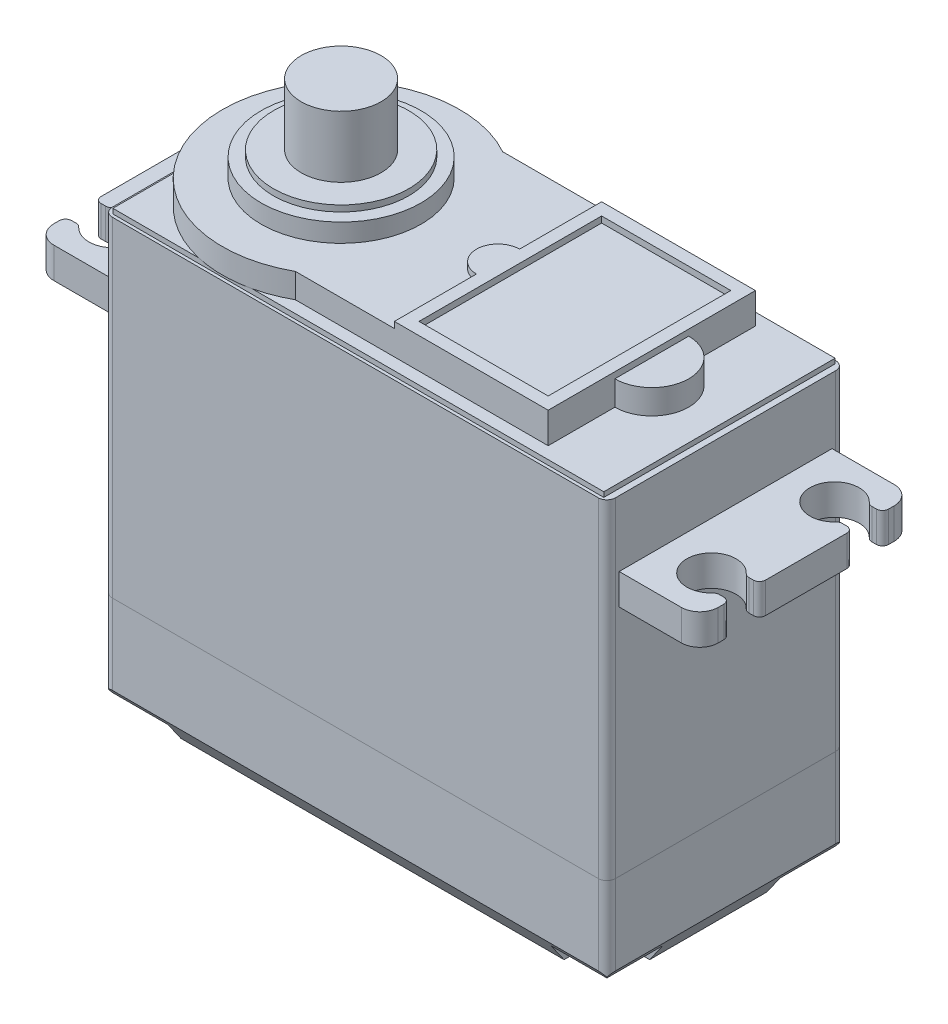
SolidWorks part; units mm, degrees
ref_plane "Front Plane" through (0, 0, 0) normal (0, 0, 1) x (1, 0, 0)
ref_plane "Top Plane" through (0, 0, 0) normal (0, 1, 0) x (1, 0, 0)
ref_plane "Right Plane" through (0, 0, 0) normal (1, 0, 0) x (0, 0, -1)
sketch "Sketch1" plane through (0, 0, 0) normal (0, 0, 1) x (1, 0, 0)
  line L1 (-20.45, 10) -> (20.45, 10)
  line L2 (-20.45, 10) -> (-20.45, -10)
  line L3 (-20.45, -10) -> (20.45, -10)
  line L4 (20.45, 10) -> (20.45, -10)
  line L5 (-20.45, 10) -> (20.45, -10) construction
  line L6 (-20.45, -10) -> (20.45, 10) construction
  point P0 (0, 0)
  dimension "D1" = 20
  dimension "D2" = 40.9
extrude "Boss-Extrude1" add sketch "Sketch1" along normal blind 19.3
sketch "Sketch2" plane through (0, 10, 0) normal (0, 1, 0) x (1, 0, 0)
  line L4 (20.45, 0) -> (-20.45, 0)
  line L5 (-20.45, 0) -> (-20.45, -19.3)
  line L6 (-20.45, -19.3) -> (20.45, -19.3)
  line L7 (20.45, -19.3) -> (20.45, 0)
  line L8 (20.45, 0) -> (-20.45, 0)
  line L9 (-20.45, 0) -> (-20.45, -19.3)
  line L10 (-20.45, -19.3) -> (20.45, -19.3)
  line L11 (20.45, -19.3) -> (20.45, 0)
  dimension "D1" = 0
extrude "Boss-Extrude2" add sketch "Sketch2" along normal blind 6.8 separate body
sketch "Sketch3" plane through (0, -10, 0) normal (0, -1, 0) x (1, 0, 0)
  line L4 (-20.45, 0) -> (20.45, 0)
  line L5 (20.45, 0) -> (20.45, 19.3)
  line L6 (20.45, 19.3) -> (-20.45, 19.3)
  line L7 (-20.45, 19.3) -> (-20.45, 0)
  line L8 (-20.45, 0) -> (20.45, 0)
  line L9 (20.45, 0) -> (20.45, 19.3)
  line L10 (20.45, 19.3) -> (-20.45, 19.3)
  line L11 (-20.45, 19.3) -> (-20.45, 0)
  dimension "D1" = 0
extrude "Boss-Extrude3" add sketch "Sketch3" along normal blind 8.5 separate body
chamfer "Chamfer1" distance 2 angle 35 4 edges at (0, -18.5, 19.3) (20.45, -18.5, 9.65) (0, -18.5, 0) (-20.45, -18.5, 9.65)
sketch "Sketch4" plane through (0, -18.5, 0) normal (0, -1, 0) x (1, 0, 0)
  line L0 (0, 0) -> (0, 19.3) construction
  line L1 (-20.45, 19.3) -> (-15.57, 19.3)
  line L2 (-20.45, 19.3) -> (-20.45, 14.42)
  line L3 (-20.45, 14.42) -> (-17.57, 14.42)
  line L4 (-15.57, 19.3) -> (-15.57, 16.42)
  line L5 (-20.45, 19.3) -> (20.45, 19.3) construction
  line L6 (-20.45, 9.65) -> (20.45, 9.65) construction
  line L7 (-20.45, 0) -> (-20.45, 19.3) construction
  line L8 (20.45, 19.3) -> (20.45, 0) construction
  line L9 (20.45, 14.42) -> (17.57, 14.42)
  line L10 (15.57, 19.3) -> (15.57, 16.42)
  line L11 (20.45, 19.3) -> (15.57, 19.3)
  line L12 (20.45, 19.3) -> (20.45, 14.42)
  line L13 (20.45, 0) -> (20.45, 4.88)
  line L14 (20.45, 0) -> (15.57, 0)
  line L15 (15.57, 0) -> (15.57, 2.88)
  line L16 (20.45, 4.88) -> (17.57, 4.88)
  line L17 (-20.45, 4.88) -> (-17.57, 4.88)
  line L18 (-15.57, 0) -> (-15.57, 2.88)
  line L19 (-20.45, 0) -> (-15.57, 0)
  line L20 (-20.45, 0) -> (-20.45, 4.88)
  arc A0 (-17.57, 14.42) -> (-15.57, 16.42) centre (-17.57, 16.42) ccw
  arc A1 (17.57, 14.42) -> (15.57, 16.42) centre (17.57, 16.42) cw
  arc A2 (17.57, 4.88) -> (15.57, 2.88) centre (17.57, 2.88) ccw
  arc A3 (-17.57, 4.88) -> (-15.57, 2.88) centre (-17.57, 2.88) cw
  dimension "D3" = 2
  dimension "D1" = 4.88
  dimension "D2" = 4.88
extrude "Cut-Extrude1" cut sketch "Sketch4" against normal blind 1.5
sketch "Sketch5" plane through (0, 16.8, 0) normal (0, 1, 0) x (1, 0, 0)
  line L0 (-20.45, -9.65) -> (20.45, -9.65) construction
  line L1 (-19.95, -0.25) -> (19.95, -0.25)
  line L2 (-19.95, -0.25) -> (-19.95, -19.05)
  line L3 (-19.95, -19.05) -> (19.95, -19.05)
  line L4 (19.95, -0.25) -> (19.95, -19.05)
  line L5 (-19.95, -0.25) -> (19.95, -19.05) construction
  line L6 (-19.95, -19.05) -> (19.95, -0.25) construction
  line L7 (-20.45, 0) -> (-20.45, -19.3) construction
  line L8 (20.45, 0) -> (-20.45, 0) construction
  line L9 (20.45, -19.3) -> (20.45, 0) construction
  point P0 (0, -9.65)
  point P9 (0, 0)
  point P10 (0, -9.65)
  point P13 (20.45, -9.65)
  dimension "D1" = 0.25
  dimension "D2" = 0.5
extrude "Boss-Extrude4" add sketch "Sketch5" along normal blind 0.4
sketch "Sketch6" plane through (0, 17.2, 0) normal (0, 1, 0) x (1, 0, 0)
  line L0 (-20.45, -9.65) -> (20.45, -9.65) construction
  line L1 (-20.45, 0) -> (-20.45, -19.3) construction
  line L2 (20.45, -19.3) -> (20.45, 0) construction
  line L3 (20.45, 0) -> (-20.45, 0) construction
  line L4 (-6.09, -0.25) -> (-6.09, -19.3) construction
  line L5 (14.45, -18.0725) -> (14.45, -12.65)
  line L6 (19.95, -0.25) -> (-19.95, -0.25) construction
  line L7 (-20.45, -19.3) -> (20.45, -19.3) construction
  line L8 (-6.09, -1.2275) -> (14.45, -1.2275)
  line L9 (14.45, -1.2275) -> (14.45, -6.65)
  line L10 (-6.09, -18.0725) -> (14.45, -18.0725)
  arc A0 (-6.09, -1.2275) -> (-6.09, -18.0725) centre (-10.8, -9.65) ccw
  arc A1 (14.45, -12.65) -> (14.45, -6.65) centre (14.45, -9.65) ccw
  point P23 (17.45, -9.65)
  dimension "D3" = 3
  dimension "D1" = 14.36
  dimension "D2" = 6
extrude "Boss-Extrude5" add sketch "Sketch6" along normal blind 2
sketch "Sketch7" plane through (0, 19.2, 0) normal (0, 1, 0) x (1, 0, 0)
  circle A0 centre (-10.8, -9.65) radius 6.5
  dimension "D1" = 13
extrude "Boss-Extrude6" add sketch "Sketch7" along normal blind 1.5
sketch "Sketch8" plane through (0, 20.7, 0) normal (0, 1, 0) x (1, 0, 0)
  circle A0 centre (-10.8, -9.65) radius 5.5
  dimension "D1" = 11
extrude "Boss-Extrude7" add sketch "Sketch8" along normal blind 0.5
sketch "Sketch9" plane through (0, 21.2, 0) normal (0, 1, 0) x (1, 0, 0)
  circle A0 centre (-10.8, -9.65) radius 3.25
  dimension "D1" = 6.5
extrude "Boss-Extrude8" add sketch "Sketch9" along normal blind 5
sketch "Sketch10" plane through (0, 19.2, 0) normal (0, 1, 0) x (1, 0, 0)
  line L0 (14.45, -1.2275) -> (-6.09, -1.2275) construction
  line L1 (1.95, -1.2275) -> (14.45, -1.2275)
  line L2 (1.95, -1.2275) -> (1.95, -7.9)
  line L3 (1.95, -18.0725) -> (14.45, -18.0725)
  line L4 (14.45, -1.2275) -> (14.45, -18.0725)
  line L5 (2.95, -2.2275) -> (13.45, -2.2275)
  line L6 (13.45, -2.2275) -> (13.45, -17.0725)
  line L7 (2.95, -17.0725) -> (13.45, -17.0725)
  line L8 (2.95, -2.2275) -> (2.95, -17.0725)
  line L9 (1.95, -11.4) -> (1.95, -18.0725)
  line L10 (1.95, -1.2275) -> (1.95, -18.0725) construction
  arc A0 (1.95, -7.9) -> (1.95, -11.4) centre (1.95, -9.65) ccw
  dimension "D3" = 3.5
  dimension "D1" = 12.5
  dimension "D2" = 1
extrude "Boss-Extrude9" add sketch "Sketch10" along normal blind 0.5
fillet "Fillet1" radius 0.7 4 edges at (20.45, 0, 0) (-20.45, 0, 0) (-20.45, 0, 19.3) (20.45, 0, 19.3)
fillet "Fillet2" radius 0.7 4 edges at (-20.45, 13.4, 0) (20.45, 13.4, 0) (-20.45, 13.4, 19.3) (20.45, 13.4, 19.3)
fillet "Fillet3" radius 0.7 4 edges at (20.45, -13.25, 0) (-20.45, -13.25, 0) (-20.45, -13.25, 19.3) (20.45, -13.25, 19.3)
sketch "Sketch11" plane through (0, 17.2, 0) normal (0, 1, 0) x (1, 0, 0)
  line L0 (20.45, -1) -> (25.5, -1)
  line L1 (20.45, -18.6) -> (20.45, -0.7) construction
  line L2 (0.2, -9.65) -> (30.4042, -9.65) construction
  line L3 (27, -2.5) -> (27, -2.95)
  line L4 (19.75, 0) -> (-19.75, 0) construction
  line L5 (0, 0) -> (0, -19.3) construction
  line L6 (-19.75, -19.3) -> (19.75, -19.3) construction
  line L7 (25.9, -1) -> (25.9, -18.3) construction
  line L8 (26.133, -5.85) -> (26.5, -5.85)
  line L9 (26.133, -3.45) -> (26.5, -3.45)
  line L10 (27, -6.35) -> (27, -12.95)
  line L11 (26.133, -15.85) -> (26.5, -15.85)
  line L12 (26.133, -13.45) -> (26.5, -13.45)
  line L13 (27, -16.8) -> (27, -16.35)
  line L14 (20.45, -18.3) -> (25.5, -18.3)
  line L15 (20.45, -1) -> (20.45, -18.3)
  arc A0 (1.95, -7.9) -> (1.95, -11.4) centre (1.95, -9.65) ccw construction
  arc A1 (25.7664, -3.29) -> (25.7664, -6.01) centre (24.3, -4.65) ccw
  arc A2 (26.5, -5.85) -> (27, -6.35) centre (26.5, -6.35) cw
  arc A3 (25.7664, -6.01) -> (26.133, -5.85) centre (26.133, -6.35) cw
  arc A4 (25.7664, -3.29) -> (26.133, -3.45) centre (26.133, -2.95) ccw
  arc A5 (26.5, -3.45) -> (27, -2.95) centre (26.5, -2.95) ccw
  arc A6 (25.5, -1) -> (27, -2.5) centre (25.5, -2.5) cw
  arc A7 (25.5, -18.3) -> (27, -16.8) centre (25.5, -16.8) ccw
  arc A8 (26.5, -15.85) -> (27, -16.35) centre (26.5, -16.35) cw
  arc A9 (25.7664, -16.01) -> (26.133, -15.85) centre (26.133, -16.35) cw
  arc A10 (25.7664, -13.29) -> (26.133, -13.45) centre (26.133, -12.95) ccw
  arc A11 (26.5, -13.45) -> (27, -12.95) centre (26.5, -12.95) ccw
  arc A12 (25.7664, -16.01) -> (25.7664, -13.29) centre (24.3, -14.65) cw
  point P27 (27, -5.85)
  point P30 (25.9, -5.85)
  point P33 (25.9, -3.45)
  point P38 (27, -1)
  point P40 (25.9, -9.65)
  point P56 (27, -9.65)
  point P57 (27, -18.3)
  point P58 (25.9, -15.85)
  point P59 (25.9, -13.45)
  point P60 (27, -13.45)
  dimension "D3" = 4
  dimension "D7" = 0.5
  dimension "D8" = 1.5
  dimension "D1" = 1
  dimension "D2" = 6.55
  dimension "D4" = 5
  dimension "D5" = 24.3
  dimension "D6" = 1.1
extrude "Boss-Extrude10" add sketch "Sketch11" against normal blind 2.5 from offset 5.74 offset against normal yes
mirror "Mirror1" about plane through (0, 0, 0) normal (1, 0, 0) of "Boss-Extrude10"
